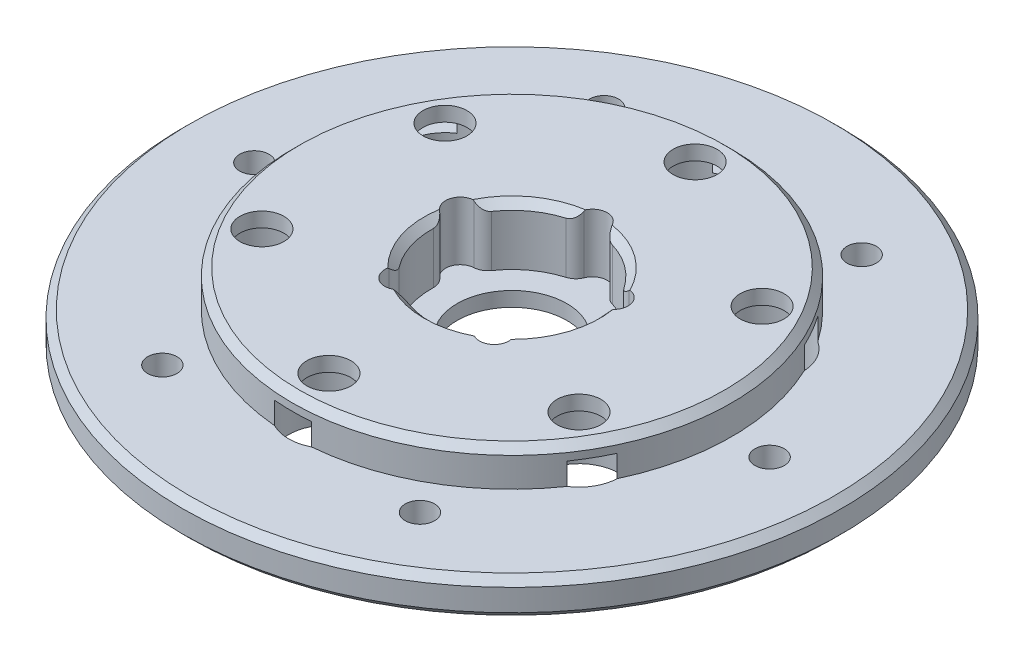
SolidWorks part; units mm, degrees
ref_plane "Front Plane" through (0, 0, 0) normal (0, 0, 1) x (1, 0, 0)
ref_plane "Top Plane" through (0, 0, 0) normal (0, 1, 0) x (1, 0, 0)
ref_plane "Right Plane" through (0, 0, 0) normal (1, 0, 0) x (0, 0, -1)
sketch "Sketch1" plane through (0, 0, 0) normal (0, 1, 0) x (1, 0, 0)
  circle A0 centre (0, 0) radius 45
  dimension "D1" = 90
extrude "Boss-Extrude1" add sketch "Sketch1" along normal blind 5
sketch "Sketch2" plane through (0, 5, 0) normal (0, 1, 0) x (1, 0, 0)
  circle A0 centre (0, 0) radius 30
  dimension "D1" = 60
extrude "Boss-Extrude2" add sketch "Sketch2" along normal blind 5
sketch "Sketch3" plane through (0, 10, 0) normal (0, 1, 0) x (1, 0, 0)
  circle A0 centre (0, 0) radius 25 construction
  circle A1 centre (0, 25) radius 3
  circle A2 centre (21.6506, 12.5) radius 3
  circle A3 centre (21.6506, -12.5) radius 3
  circle A4 centre (0, -25) radius 3
  circle A5 centre (-21.6506, -12.5) radius 3
  circle A6 centre (-21.6506, 12.5) radius 3
  point P17 (0, 0)
  dimension "D1" = 50
  dimension "D2" = 6
  dimension "D3" = 6
extrude "Cut-Extrude1" cut sketch "Sketch3" against normal blind 25
sketch "Sketch4" plane through (0, 10, 0) normal (0, 1, 0) x (1, 0, 0)
  arc A0 (-1.9917, 10.8182) -> (-9.6732, 5.2372) centre (0, 0) ccw
  arc A1 (1.9917, 10.8182) -> (-1.9917, 10.8182) centre (0, 11) ccw
  arc A2 (10.9042, 1.4488) -> (9.6732, 5.2372) centre (10.4616, 3.3992) ccw
  arc A3 (4.7474, -9.9228) -> (7.9701, -7.5814) centre (6.4656, -8.8992) ccw
  arc A4 (-7.9701, -7.5814) -> (-4.7474, -9.9228) centre (-6.4656, -8.8992) ccw
  arc A5 (-9.6732, 5.2372) -> (-10.9042, 1.4488) centre (-10.4616, 3.3992) ccw
  arc A6 (9.6732, 5.2372) -> (1.9917, 10.8182) centre (0, 0) ccw
  arc A7 (7.9701, -7.5814) -> (10.9042, 1.4488) centre (0, 0) ccw
  arc A8 (-4.7474, -9.9228) -> (4.7474, -9.9228) centre (0, 0) ccw
  arc A9 (-10.9042, 1.4488) -> (-7.9701, -7.5814) centre (0, 0) ccw
  point P15 (0, 0)
  dimension "D1" = 22
  dimension "D2" = 5
extrude "Cut-Extrude2" cut sketch "Sketch4" against normal blind 8
sketch "Sketch5" plane through (0, 2, 0) normal (0, 1, 0) x (1, 0, 0)
  circle A0 centre (0, 0) radius 7.5
  dimension "D1" = 15
extrude "Cut-Extrude3" cut sketch "Sketch5" against normal blind 5
chamfer "Chamfer1" distance 1 angle 45 3 edges at (0, 0, 45) (0, 5, 45) (0, 10, 30)
sketch "Sketch6" plane through (0, 0, 0) normal (0, -1, 0) x (1, 0, 0)
  circle A0 centre (0, 0) radius 25 construction
  circle A1 centre (0, 25) radius 5.5
  circle A2 centre (21.6506, 12.5) radius 5.5
  circle A3 centre (21.6506, -12.5) radius 5.5
  circle A4 centre (0, -25) radius 5.5
  circle A5 centre (-21.6506, -12.5) radius 5.5
  circle A6 centre (-21.6506, 12.5) radius 5.5
  point P18 (0, 0)
  dimension "D1" = 11
  dimension "D2" = 6
extrude "Cut-Extrude8" cut sketch "Sketch6" against normal blind 8
chamfer "Chamfer2" distance 1 angle 45 5 edges at (0, 10, 11) (10.4616, 10, 3.3992) (6.4656, 10, -8.8992) (-6.4656, 10, -8.8992) (-10.4616, 10, 3.3992)
sketch "Sketch7" plane through (0, 0, 0) normal (0, -1, 0) x (1, 0, 0)
  circle A0 centre (0, 0) radius 35 construction
  circle A1 centre (17.6532, 30.2219) radius 2
  circle A2 centre (34.9996, -0.1772) radius 2
  circle A3 centre (17.3463, -30.3991) radius 2
  circle A4 centre (-17.6532, -30.2219) radius 2
  circle A5 centre (-34.9996, 0.1772) radius 2
  circle A6 centre (-17.3463, 30.3991) radius 2
  point P17 (0, 0)
  dimension "D1" = 4
  dimension "D2" = 6
extrude "Cut-Extrude5" cut sketch "Sketch7" against normal blind 28
fillet "Fillet1" radius 2 10 edges at (-4.7474, 5.5, 9.9228) (4.7474, 5.5, 9.9228) (7.9701, 5.5, 7.5814) (10.9042, 5.5, -1.4488) (9.6732, 5.5, -5.2372) (1.9917, 5.5, -10.8182) (-1.9917, 5.5, -10.8182) (-9.6732, 5.5, -5.2372) (-10.9042, 5.5, -1.4488) (-7.9701, 5.5, 7.5814)
